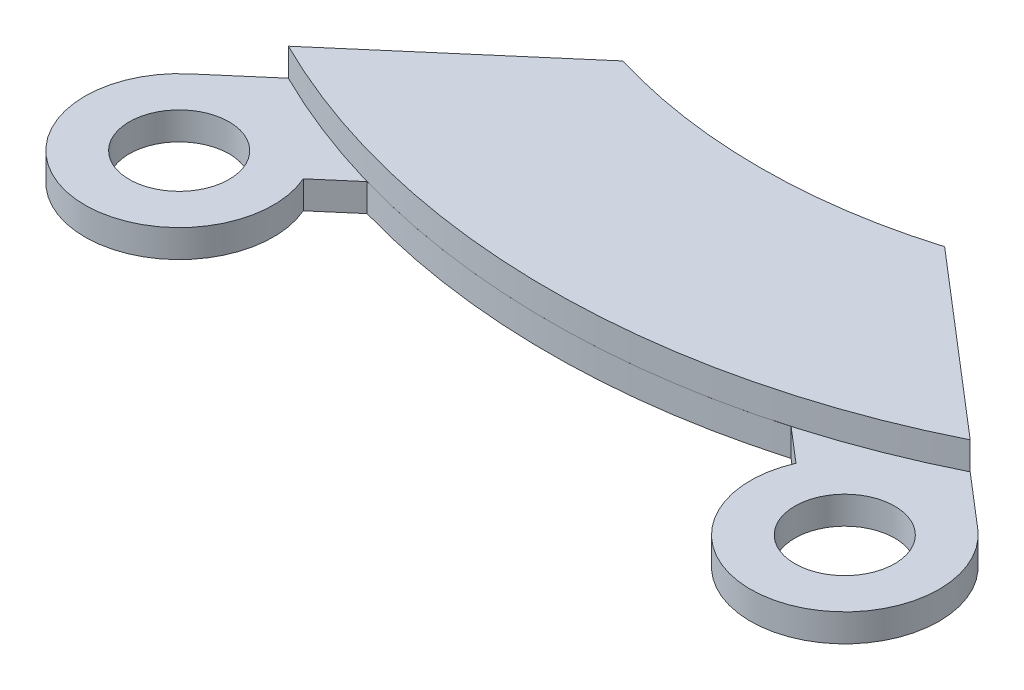
SolidWorks part; units mm, degrees
material "Leaded Commercial Bronze"
ref_plane "Front Plane" through (0, 0, 0) normal (0, 0, 1) x (1, 0, 0)
ref_plane "Top Plane" through (0, 0, 0) normal (0, 1, 0) x (1, 0, 0)
ref_plane "Right Plane" through (0, 0, 0) normal (1, 0, 0) x (0, 0, -1)
sketch "Sketch1" plane through (0, 0, 0) normal (0, 1, 0) x (1, 0, 0)
  line L0 (0, 28.3862) -> (0, 0) construction
  line L1 (45.1296, 8.1925) -> (18.415, 31.115)
  line L2 (28.2023, 4.3091) -> (24.2692, 7.6839)
  line L3 (-28.2023, 4.3091) -> (-24.2692, 7.6839)
  line L4 (-45.1296, 8.1925) -> (-18.415, 31.115)
  circle A0 centre (38.1, 0) radius 5.715
  arc A1 (-18.415, 31.115) -> (18.415, 31.115) centre (0, 91.8862) ccw
  arc A2 (28.2023, 4.3091) -> (45.1296, 8.1925) centre (38.1, 0) ccw
  arc A3 (-28.2023, 4.3091) -> (-45.1296, 8.1925) centre (-38.1, 0) cw
  circle A4 centre (-38.1, 0) radius 5.715
  circle A5 centre (38.1, 0) radius 10.795 construction
  arc A6 (-24.2692, 7.6839) -> (24.2692, 7.6839) centre (0, 91.8862) ccw
  point P11 (38.1, -10.795)
  point P21 (-38.1, -10.795)
  dimension "D2" = 11.43
  dimension "D3" = 127
  dimension "D7" = 24.13
  dimension "D1" = 76.2
  dimension "D5" = 36.83
  dimension "D6" = 41.91
  dimension "D8" = 13.97
  dimension "D4" = 5.08
extrude "Boss-Extrude1" add sketch "Sketch1" along normal blind 3.175
sketch "Sketch2" plane through (0, 3.175, 0) normal (0, 1, 0) x (1, 0, 0)
  line L0 (-18.415, 31.115) -> (-45.1296, 8.1925) construction
  line L1 (45.1296, 8.1925) -> (18.415, 31.115) construction
  line L2 (-18.415, 31.115) -> (-39.0287, 13.4274)
  line L3 (39.0287, 13.4274) -> (18.415, 31.115)
  arc A0 (-18.415, 31.115) -> (18.415, 31.115) centre (0, 91.8862) ccw construction
  arc A1 (-18.415, 31.115) -> (18.415, 31.115) centre (0, 91.8862) ccw
  arc A2 (-39.0287, 13.4274) -> (39.0287, 13.4274) centre (0, 91.8862) ccw
  arc A3 (-24.2692, 7.6839) -> (24.2692, 7.6839) centre (0, 91.8862) ccw construction
extrude "Boss-Extrude2" add sketch "Sketch2" along normal blind 3.175 separate body
